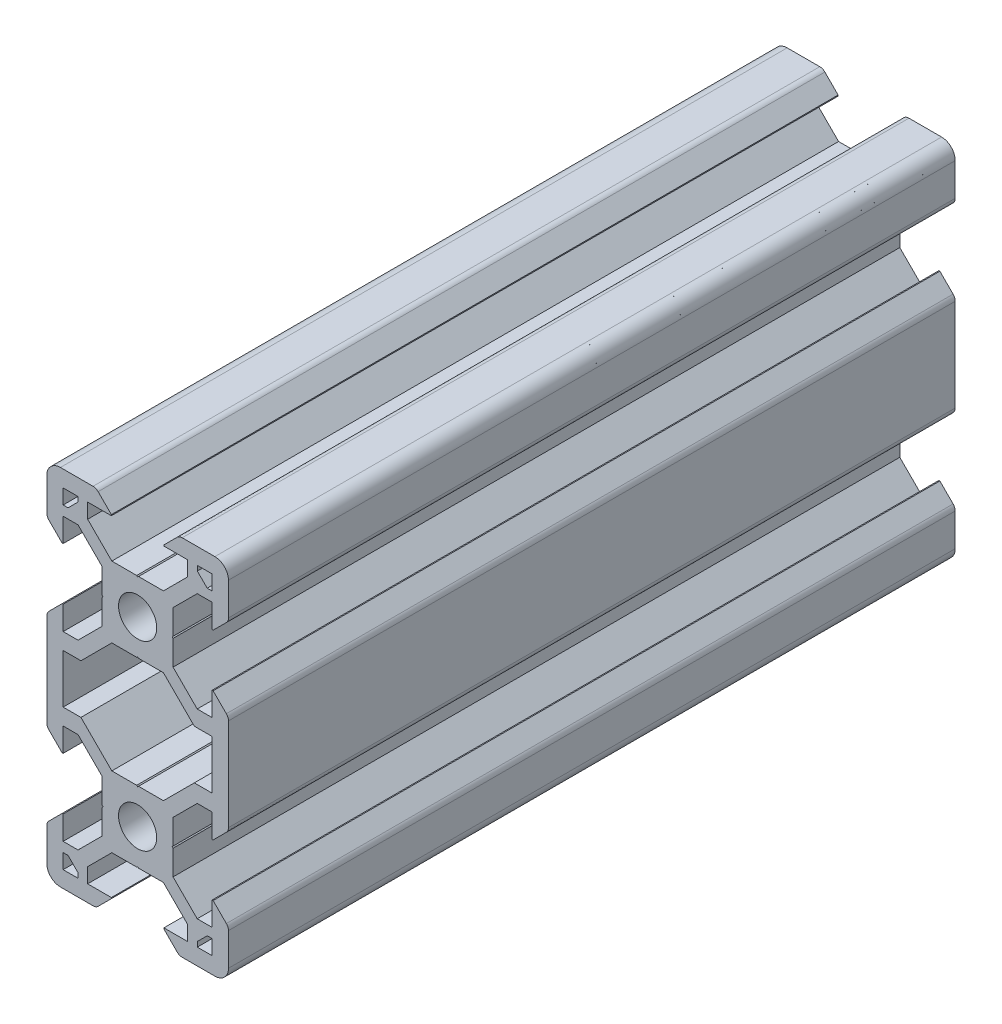
SolidWorks part; units mm, degrees
ref_plane "Front Plane" through (0, 0, 0) normal (0, 0, 1) x (1, 0, 0)
ref_plane "Top Plane" through (0, 0, 0) normal (0, 1, 0) x (1, 0, 0)
ref_plane "Right Plane" through (0, 0, 0) normal (1, 0, 0) x (0, 0, -1)
sketch "Sketch1" plane through (0, 0, 0) normal (0, 0, 1) x (1, 0, 0)
  line L0 (-8.2, 2.8875) -> (-8.2, 5.4975)
  line L3 (-4.9072, 9.9975) -> (-8.5, 9.9975)
  line L4 (-10, 4.9047) -> (-10, 8.4975)
  line L5 (-2.1, 0) -> (-3.8, 0) construction
  line L6 (0, 3.8) -> (0, 0) construction
  line L7 (-0.1, 3.9) -> (-2.8404, 3.9)
  line L8 (-3.9, 0.1) -> (-3.9, 2.8383)
  line L9 (-2.89, 8.1975) -> (-5.5, 8.1975)
  line L10 (-6.57, 8.1975) -> (-6.57, 7.6575)
  line L11 (-8.2, 6.5675) -> (-7.66, 6.5675)
  line L12 (-5.5, 8.1975) -> (-5.5, 6.5588)
  line L13 (-6.56, 5.4975) -> (-8.2, 5.4975)
  line L14 (-8.2, 8.1975) -> (-1.4852, 1.4847) construction
  line L15 (-6.56, 5.4975) -> (-3.9, 2.8383)
  line L16 (-5.5, 6.5588) -> (-2.8404, 3.9)
  line L17 (-7.66, 6.5675) -> (-6.57, 7.6575)
  line L18 (-8.7302, 7.6671) -> (-0.5302, -0.5304) construction
  line L19 (-7.6698, 8.7279) -> (0.5302, 0.5304) construction
  line L20 (-8.2, 8.1975) -> (0, 0) construction
  line L21 (-8.2, 6.5675) -> (-8.2, 8.1975)
  line L22 (-8.2, -0.0025) -> (-8.2, 8.1975) construction
  line L23 (-6.57, 8.1975) -> (-8.2, 8.1975)
  line L24 (0, 8.1975) -> (-8.2, 8.1975) construction
  line L25 (-10, -0.0025) -> (-10, 9.9975) construction
  line L26 (0, 9.9975) -> (-10, 9.9975) construction
  line L27 (-2.89, 8.3075) -> (-2.89, 8.1975)
  line L29 (-8.31, 2.8875) -> (-8.2, 2.8875)
  line L30 (-4.3486, 9.7661) -> (-2.89, 8.3075)
  line L31 (-8.31, 2.8875) -> (-9.7686, 4.3461)
  line L34 (-0.1, 3.9) -> (0, 3.8)
  line L35 (-3.9, 0.1) -> (-3.8, 0)
  line L36 (-8.2, -7.2996) -> (-6.24, -7.2996)
  line L37 (0, 0) -> (0, -10) construction
  line L38 (-0.1, -3.9) -> (-2.8404, -3.9)
  line L39 (-3.8, 0) -> (-3.9, -0.1)
  line L40 (-3.9, -0.1) -> (-3.9, -2.84)
  line L41 (-2.8404, -3.9) -> (-6.24, -7.2996)
  line L42 (-3.9, -2.84) -> (-6.56, -5.5)
  line L43 (-8.2, -2.89) -> (-8.2, -5.5)
  line L44 (-6.56, 5.4975) -> (-6.56, -5.5) construction
  line L45 (-6.56, -5.5) -> (-8.2, -5.5)
  line L46 (-0.1, -3.9) -> (0, -3.8)
  line L48 (-8.2, -2.89) -> (-8.31, -2.89)
  line L49 (-8.31, -2.89) -> (-9.7657, -4.3457)
  line L52 (-10, -10) -> (0, -10) construction
  line L53 (-8.2, -7.2996) -> (-8.2, -10)
  line L61 (-10, -4.9114) -> (-10, -10)
  arc A1 (-10, 8.4975) -> (-8.5, 9.9975) centre (-8.5, 8.4975) cw
  arc A2 (-9.7686, 4.3461) -> (-10, 4.9047) centre (-9.21, 4.9047) cw
  arc A3 (-4.3486, 9.7661) -> (-4.9072, 9.9975) centre (-4.9072, 9.2075) ccw
  arc A4 (-9.7657, -4.3457) -> (-10, -4.9114) centre (-9.2, -4.9114) ccw
  arc A6 (0, 2.1) -> (0, -2.1) centre (0, 0) ccw
  point P29 (-10, 9.9975)
  point P39 (-10, 4.5775)
  point P42 (-4.58, 9.9975)
  point P48 (-10, -4.58)
  dimension "D15" = 1.5
  dimension "D22" = 0.79
  dimension "D30" = 1.96
  dimension "D31" = 2.1
  dimension "D39" = 0.8
  dimension "D4" = 1.8
  dimension "D5" = 3.43
  dimension "D6" = 3.43
  dimension "D7" = 0.54
  dimension "D8" = 0.54
  dimension "D9" = 1.07
  dimension "D10" = 1.07
  dimension "D11" = 3.9
  dimension "D12" = 3.9
  dimension "D16" = 7.11
  dimension "D17" = 0.11
  dimension "D18" = 1.69
  dimension "D19" = 0.11
  dimension "D20" = 7.11
  dimension "D21" = 1.69
  dimension "D23" = 10
  dimension "D24" = 0.1
  dimension "D25" = 45
  dimension "D26" = 0.1
  dimension "D27" = 45
  dimension "D28" = 1.64
  dimension "D29" = 10
  dimension "D32" = 3.9
  dimension "D33" = 45
  dimension "D34" = 2.74
  dimension "D35" = 45
  dimension "D37" = 2.61
  dimension "D38" = 90
  dimension "D40" = 0.1
  dimension "D41" = 45
  dimension "D13" = 0.75
  dimension "D14" = 0.75
sketch "Sketch2" plane through (0, 0, 0) normal (0, 0, 1) x (1, 0, 0)
  line L0 (-0.1, 3.9) -> (0, 3.8) construction
  line L1 (-0.1, 3.9) -> (-2.8404, 3.9) construction
  line L2 (-5.5, 6.5588) -> (-2.8404, 3.9) construction
  line L3 (-5.5, 8.1975) -> (-5.5, 6.5588) construction
  line L4 (-2.89, 8.1975) -> (-5.5, 8.1975) construction
  line L5 (-7.66, 6.5675) -> (-6.57, 7.6575)
  line L6 (-6.57, 7.6575) -> (-6.57, 8.1975)
  line L7 (-6.57, 8.1975) -> (-8.2, 8.1975)
  line L8 (-8.2, 8.1975) -> (-8.2, 6.5675)
  line L9 (-8.2, 6.5675) -> (-7.66, 6.5675)
  line L10 (-7.66, 6.5675) -> (-6.57, 7.6575)
  line L11 (-6.57, 7.6575) -> (-6.57, 8.1975)
  line L12 (-6.57, 8.1975) -> (-8.2, 8.1975)
  line L13 (-8.2, 8.1975) -> (-8.2, 6.5675)
  line L14 (-8.2, 6.5675) -> (-7.66, 6.5675)
  line L15 (-2.89, 8.3075) -> (-2.89, 8.1975) construction
  line L16 (-4.3486, 9.7661) -> (-2.89, 8.3075) construction
  line L17 (-4.9072, 9.9975) -> (-8.5, 9.9975) construction
  line L18 (-10, 4.9047) -> (-10, 8.4975) construction
  line L19 (-8.31, 2.8875) -> (-9.7686, 4.3461) construction
  line L20 (-8.31, 2.8875) -> (-8.2, 2.8875) construction
  line L21 (-8.2, 2.8875) -> (-8.2, 5.4975) construction
  line L22 (-6.56, 5.4975) -> (-8.2, 5.4975) construction
  line L23 (-6.56, 5.4975) -> (-3.9, 2.8383) construction
  line L24 (-3.9, 0.1) -> (-3.9, 2.8383) construction
  line L25 (-3.9, 0.1) -> (-3.8, 0) construction
  line L26 (-3.8, 0) -> (-3.9, -0.1) construction
  line L27 (-3.9, -0.1) -> (-3.9, -2.84) construction
  line L28 (-3.9, -2.84) -> (-6.56, -5.5) construction
  line L29 (-6.56, -5.5) -> (-8.2, -5.5) construction
  line L30 (-8.2, -2.89) -> (-8.2, -5.5) construction
  line L31 (-8.2, -2.89) -> (-8.31, -2.89) construction
  line L32 (-8.31, -2.89) -> (-9.7657, -4.3457) construction
  line L33 (-10, -4.9114) -> (-10, -10) construction
  line L34 (-0.1, -3.9) -> (0, -3.8) construction
  line L35 (-0.1, -3.9) -> (-2.8404, -3.9) construction
  line L36 (-2.8404, -3.9) -> (-6.24, -7.2996) construction
  line L37 (-8.2, -7.2996) -> (-6.24, -7.2996) construction
  line L38 (-8.2, -7.2996) -> (-8.2, -10) construction
  line L39 (-0.1, 3.9) -> (0, 3.8)
  line L40 (-0.1, 3.9) -> (-2.8404, 3.9)
  line L41 (-5.5, 6.5588) -> (-2.8404, 3.9)
  line L42 (-5.5, 8.1975) -> (-5.5, 6.5588)
  line L43 (-2.89, 8.1975) -> (-5.5, 8.1975)
  line L44 (-2.89, 8.3075) -> (-2.89, 8.1975)
  line L45 (-4.3486, 9.7661) -> (-2.89, 8.3075)
  line L46 (-4.9072, 9.9975) -> (-8.5, 9.9975)
  line L47 (-10, 4.9047) -> (-10, 8.4975)
  line L48 (-8.31, 2.8875) -> (-9.7686, 4.3461)
  line L49 (-8.31, 2.8875) -> (-8.2, 2.8875)
  line L50 (-8.2, 2.8875) -> (-8.2, 5.4975)
  line L51 (-6.56, 5.4975) -> (-8.2, 5.4975)
  line L52 (-6.56, 5.4975) -> (-3.9, 2.8383)
  line L53 (-3.9, 0.1) -> (-3.9, 2.8383)
  line L54 (-3.9, 0.1) -> (-3.8, 0)
  line L55 (-3.8, 0) -> (-3.9, -0.1)
  line L56 (-3.9, -0.1) -> (-3.9, -2.84)
  line L57 (-3.9, -2.84) -> (-6.56, -5.5)
  line L58 (-6.56, -5.5) -> (-8.2, -5.5)
  line L59 (-8.2, -2.89) -> (-8.2, -5.5)
  line L60 (-8.2, -2.89) -> (-8.31, -2.89)
  line L61 (-8.31, -2.89) -> (-9.7657, -4.3457)
  line L62 (-10, -4.9114) -> (-10, -15.0886)
  line L63 (-0.1, -3.9) -> (0, -3.8)
  line L64 (-0.1, -3.9) -> (-2.8404, -3.9)
  line L65 (-2.8404, -3.9) -> (-6.24, -7.2996)
  line L66 (-8.2, -7.2996) -> (-6.24, -7.2996)
  line L67 (-8.2, -7.2996) -> (-8.2, -12.7004)
  line L68 (0, 0) -> (0, -10) construction
  line L69 (-10, -10) -> (0, -10) construction
  line L70 (0, 0) -> (0, -20) construction
  line L71 (-10, -10) -> (10, -10) construction
  line L72 (8.2, -7.2996) -> (8.2, -12.7004)
  line L73 (8.2, -7.2996) -> (6.24, -7.2996)
  line L74 (2.8404, -3.9) -> (6.24, -7.2996)
  line L75 (0.1, -3.9) -> (2.8404, -3.9)
  line L76 (0.1, -3.9) -> (0, -3.8)
  line L77 (10, -4.9114) -> (10, -15.0886)
  line L78 (8.31, -2.89) -> (9.7657, -4.3457)
  line L79 (8.2, -2.89) -> (8.31, -2.89)
  line L80 (8.2, -2.89) -> (8.2, -5.5)
  line L81 (6.56, -5.5) -> (8.2, -5.5)
  line L82 (3.9, -2.84) -> (6.56, -5.5)
  line L83 (3.9, -0.1) -> (3.9, -2.84)
  line L84 (3.8, 0) -> (3.9, -0.1)
  line L85 (3.9, 0.1) -> (3.8, 0)
  line L86 (3.9, 0.1) -> (3.9, 2.8383)
  line L87 (6.56, 5.4975) -> (3.9, 2.8383)
  line L88 (6.56, 5.4975) -> (8.2, 5.4975)
  line L89 (8.2, 2.8875) -> (8.2, 5.4975)
  line L90 (8.31, 2.8875) -> (8.2, 2.8875)
  line L91 (8.31, 2.8875) -> (9.7686, 4.3461)
  line L92 (10, 4.9047) -> (10, 8.4975)
  line L93 (4.9072, 9.9975) -> (8.5, 9.9975)
  line L94 (4.3486, 9.7661) -> (2.89, 8.3075)
  line L95 (2.89, 8.3075) -> (2.89, 8.1975)
  line L96 (2.89, 8.1975) -> (5.5, 8.1975)
  line L97 (5.5, 8.1975) -> (5.5, 6.5588)
  line L98 (5.5, 6.5588) -> (2.8404, 3.9)
  line L99 (0.1, 3.9) -> (2.8404, 3.9)
  line L100 (0.1, 3.9) -> (0, 3.8)
  line L101 (8.2, 6.5675) -> (7.66, 6.5675)
  line L102 (8.2, 8.1975) -> (8.2, 6.5675)
  line L103 (6.57, 8.1975) -> (8.2, 8.1975)
  line L104 (6.57, 7.6575) -> (6.57, 8.1975)
  line L105 (7.66, 6.5675) -> (6.57, 7.6575)
  line L106 (7.66, -26.5675) -> (6.57, -27.6575)
  line L107 (6.57, -27.6575) -> (6.57, -28.1975)
  line L108 (6.57, -28.1975) -> (8.2, -28.1975)
  line L109 (8.2, -28.1975) -> (8.2, -26.5675)
  line L110 (8.2, -26.5675) -> (7.66, -26.5675)
  line L111 (0.1, -23.9) -> (0, -23.8)
  line L112 (0.1, -23.9) -> (2.8404, -23.9)
  line L113 (5.5, -26.5588) -> (2.8404, -23.9)
  line L114 (5.5, -28.1975) -> (5.5, -26.5588)
  line L115 (2.89, -28.1975) -> (5.5, -28.1975)
  line L116 (2.89, -28.3075) -> (2.89, -28.1975)
  line L117 (4.3486, -29.7661) -> (2.89, -28.3075)
  line L118 (4.9072, -29.9975) -> (8.5, -29.9975)
  line L119 (10, -24.9047) -> (10, -28.4975)
  line L120 (8.31, -22.8875) -> (9.7686, -24.3461)
  line L121 (8.31, -22.8875) -> (8.2, -22.8875)
  line L122 (8.2, -22.8875) -> (8.2, -25.4975)
  line L123 (6.56, -25.4975) -> (8.2, -25.4975)
  line L124 (6.56, -25.4975) -> (3.9, -22.8383)
  line L125 (3.9, -20.1) -> (3.9, -22.8383)
  line L126 (3.9, -20.1) -> (3.8, -20)
  line L127 (3.8, -20) -> (3.9, -19.9)
  line L128 (3.9, -19.9) -> (3.9, -17.16)
  line L129 (3.9, -17.16) -> (6.56, -14.5)
  line L130 (6.56, -14.5) -> (8.2, -14.5)
  line L131 (8.2, -17.11) -> (8.2, -14.5)
  line L132 (8.2, -17.11) -> (8.31, -17.11)
  line L133 (8.31, -17.11) -> (9.7657, -15.6543)
  line L134 (0.1, -16.1) -> (0, -16.2)
  line L135 (0.1, -16.1) -> (2.8404, -16.1)
  line L136 (2.8404, -16.1) -> (6.24, -12.7004)
  line L137 (8.2, -12.7004) -> (6.24, -12.7004)
  line L138 (-8.2, -12.7004) -> (-6.24, -12.7004)
  line L139 (-2.8404, -16.1) -> (-6.24, -12.7004)
  line L140 (-0.1, -16.1) -> (-2.8404, -16.1)
  line L141 (-0.1, -16.1) -> (0, -16.2)
  line L142 (-8.31, -17.11) -> (-9.7657, -15.6543)
  line L143 (-8.2, -17.11) -> (-8.31, -17.11)
  line L144 (-8.2, -17.11) -> (-8.2, -14.5)
  line L145 (-6.56, -14.5) -> (-8.2, -14.5)
  line L146 (-3.9, -17.16) -> (-6.56, -14.5)
  line L147 (-3.9, -19.9) -> (-3.9, -17.16)
  line L148 (-3.8, -20) -> (-3.9, -19.9)
  line L149 (-3.9, -20.1) -> (-3.8, -20)
  line L150 (-3.9, -20.1) -> (-3.9, -22.8383)
  line L151 (-6.56, -25.4975) -> (-3.9, -22.8383)
  line L152 (-6.56, -25.4975) -> (-8.2, -25.4975)
  line L153 (-8.2, -22.8875) -> (-8.2, -25.4975)
  line L154 (-8.31, -22.8875) -> (-8.2, -22.8875)
  line L155 (-8.31, -22.8875) -> (-9.7686, -24.3461)
  line L156 (-10, -24.9047) -> (-10, -28.4975)
  line L157 (-4.9072, -29.9975) -> (-8.5, -29.9975)
  line L158 (-4.3486, -29.7661) -> (-2.89, -28.3075)
  line L159 (-2.89, -28.3075) -> (-2.89, -28.1975)
  line L160 (-2.89, -28.1975) -> (-5.5, -28.1975)
  line L161 (-5.5, -28.1975) -> (-5.5, -26.5588)
  line L162 (-5.5, -26.5588) -> (-2.8404, -23.9)
  line L163 (-0.1, -23.9) -> (-2.8404, -23.9)
  line L164 (-0.1, -23.9) -> (0, -23.8)
  line L165 (-8.2, -26.5675) -> (-7.66, -26.5675)
  line L166 (-8.2, -28.1975) -> (-8.2, -26.5675)
  line L167 (-6.57, -28.1975) -> (-8.2, -28.1975)
  line L168 (-6.57, -27.6575) -> (-6.57, -28.1975)
  line L169 (-7.66, -26.5675) -> (-6.57, -27.6575)
  arc A0 (0, 2.1) -> (0, -2.1) centre (0, 0) ccw construction
  arc A1 (-4.3486, 9.7661) -> (-4.9072, 9.9975) centre (-4.9072, 9.2075) ccw construction
  arc A2 (-8.5, 9.9975) -> (-10, 8.4975) centre (-8.5, 8.4975) ccw construction
  arc A3 (-10, 4.9047) -> (-9.7686, 4.3461) centre (-9.21, 4.9047) ccw construction
  arc A4 (-9.7657, -4.3457) -> (-10, -4.9114) centre (-9.2, -4.9114) ccw construction
  circle A5 centre (0, 0) radius 2.1
  arc A6 (-4.3486, 9.7661) -> (-4.9072, 9.9975) centre (-4.9072, 9.2075) ccw
  arc A7 (-8.5, 9.9975) -> (-10, 8.4975) centre (-8.5, 8.4975) ccw
  arc A8 (-10, 4.9047) -> (-9.7686, 4.3461) centre (-9.21, 4.9047) ccw
  arc A9 (-9.7657, -4.3457) -> (-10, -4.9114) centre (-9.2, -4.9114) ccw
  arc A10 (9.7657, -4.3457) -> (10, -4.9114) centre (9.2, -4.9114) cw
  arc A11 (10, 4.9047) -> (9.7686, 4.3461) centre (9.21, 4.9047) cw
  arc A12 (8.5, 9.9975) -> (10, 8.4975) centre (8.5, 8.4975) cw
  arc A13 (4.3486, 9.7661) -> (4.9072, 9.9975) centre (4.9072, 9.2075) cw
  arc A14 (4.3486, -29.7661) -> (4.9072, -29.9975) centre (4.9072, -29.2075) ccw
  arc A15 (8.5, -29.9975) -> (10, -28.4975) centre (8.5, -28.4975) ccw
  arc A16 (10, -24.9047) -> (9.7686, -24.3461) centre (9.21, -24.9047) ccw
  arc A17 (9.7657, -15.6543) -> (10, -15.0886) centre (9.2, -15.0886) ccw
  arc A18 (-9.7657, -15.6543) -> (-10, -15.0886) centre (-9.2, -15.0886) cw
  arc A19 (-10, -24.9047) -> (-9.7686, -24.3461) centre (-9.21, -24.9047) cw
  arc A20 (-8.5, -29.9975) -> (-10, -28.4975) centre (-8.5, -28.4975) cw
  arc A21 (-4.3486, -29.7661) -> (-4.9072, -29.9975) centre (-4.9072, -29.2075) cw
  circle A22 centre (0, -20) radius 2.1
  point P147 (8.2, -10)
  dimension "D1" = 0
extrude "Boss-Extrude1" add sketch "Sketch2" against normal blind 80
